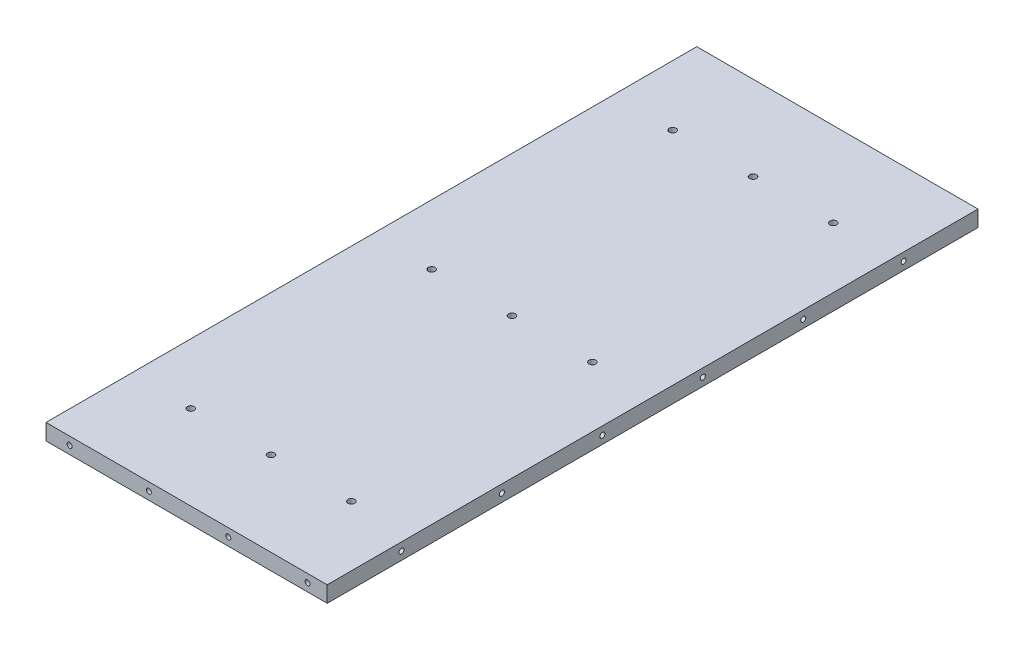
SolidWorks part; units mm, degrees
ref_plane "Front Plane" through (0, 0, 0) normal (0, 0, 1) x (1, 0, 0)
ref_plane "Top Plane" through (0, 0, 0) normal (0, 1, 0) x (1, 0, 0)
ref_plane "Right Plane" through (0, 0, 0) normal (1, 0, 0) x (0, 0, -1)
sketch "Sketch1" plane through (0, 0, 0) normal (0, 1, 0) x (1, 0, 0)
  line L1 (70, -162) -> (-70, -162)
  line L2 (70, -162) -> (70, 162)
  line L3 (70, 162) -> (-70, 162)
  line L4 (-70, -162) -> (-70, 162)
  line L5 (70, -162) -> (-70, 162) construction
  line L6 (70, 162) -> (-70, -162) construction
  point P0 (0, 0)
  dimension "D1" = 324
  dimension "D2" = 140
extrude "Boss-Extrude1" add sketch "Sketch1" along normal blind 8
sketch "Sketch2" plane through (0, 0, 162) normal (0, 0, 1) x (1, 0, 0)
  point P0 (60.25, 4)
  point P2 (20.75, 4)
  point P4 (-18.75, 4)
  point P6 (-58.25, 4)
  point P8 (-78, 4)
  point P10 (-78, 4)
  point P12 (-78, 4)
  point P14 (-78, 4)
  point P16 (-78, 4)
  point P18 (-78, 4)
hole_wizard "M3x0.5 Tapped Hole1" positions "Sketch3" profile "Sketch5" tap size "M3x0.5" standard "BSI"
sketch "Sketch3" plane through (0, 0, 162) normal (0, 0, 1) x (1, 0, 0)
  point P0 (60.25, 4)
  point P3 (20.75, 4)
  point P6 (-18.75, 4)
  point P9 (-58.25, 4)
sketch "Sketch5" plane through (60.25, 4, 162) normal (1, 0, 0) x (0, -1, 0)
  line L0 (0, 0) -> (0, 12.2511)
  line L1 (0, 12.2511) -> (1.25, 11.5)
  line L2 (1.25, 11.5) -> (1.25, 0)
  line L5 (1.25, 0) -> (0, 0)
  line L10 (0, 12.2511) -> (-1.25, 11.5) construction
  line L11 (0, -6.35) -> (0, 107.95) construction
  dimension "Tap Drill Dia." = 2.5
  dimension "Tap Drill Depth" = 11.5
  dimension "Drill Angle" = 118
cosmetic thread "Hole Thread1" parameters "D1"=10, "D2"=3.5
cosmetic thread "Hole Thread2" parameters "D1"=10, "D2"=3.5
cosmetic thread "Hole Thread3" parameters "D1"=10, "D2"=3.5
cosmetic thread "Hole Thread4" parameters "D1"=10, "D2"=3.5
sketch "Sketch6" plane through (-70, 0, 0) normal (-1, 0, 0) x (0, 0, 1)
  point P0 (125, 4)
  point P2 (75, 4)
  point P4 (25, 4)
  point P6 (-25, 4)
  point P8 (-75, 4)
  point P10 (-125, 4)
hole_wizard "M3x0.5 Tapped Hole2" positions "3DSketch1" profile "Sketch7" tap size "M3x0.5" standard "BSI"
sketch3d "3DSketch1"
  point P0 (-70, 4, -125)
  point P3 (-70, 4, -75)
  point P6 (-70, 4, -25)
  point P9 (-70, 4, 25)
  point P12 (-70, 4, 75)
  point P15 (-70, 4, 125)
sketch "Sketch7" plane through (-70, 4, -125) normal (0, 1, 0) x (0, 0, 1)
  line L0 (0, 0) -> (0, 12.2511)
  line L1 (0, 12.2511) -> (1.25, 11.5)
  line L2 (1.25, 11.5) -> (1.25, 0)
  line L5 (1.25, 0) -> (0, 0)
  line L10 (0, 12.2511) -> (-1.25, 11.5) construction
  line L11 (0, -6.35) -> (0, 107.95) construction
  dimension "Tap Drill Dia." = 2.5
  dimension "Tap Drill Depth" = 11.5
  dimension "Drill Angle" = 118
cosmetic thread "Hole Thread5" parameters "D1"=10, "D2"=3.5
cosmetic thread "Hole Thread6" parameters "D1"=10, "D2"=3.5
cosmetic thread "Hole Thread7" parameters "D1"=10, "D2"=3.5
cosmetic thread "Hole Thread8" parameters "D1"=10, "D2"=3.5
cosmetic thread "Hole Thread9" parameters "D1"=10, "D2"=3.5
cosmetic thread "Hole Thread10" parameters "D1"=10, "D2"=3.5
mirror "Mirror1" about plane through (0, 0, 0) normal (0, 0, 1) of "M3x0.5 Tapped Hole1"
mirror "Mirror2" about plane through (0, 0, 0) normal (1, 0, 0) of "M3x0.5 Tapped Hole2"
sketch "Sketch8" plane through (0, 8, 0) normal (0, 1, 0) x (1, 0, 0)
  point P0 (-40, 0)
  dimension "D1" = 40
hole_wizard "Ø3.4 (3.4) Diameter Hole1" positions "3DSketch2" profile "Sketch9" hole size "Ø3.4" standard "BSI" end condition through all
sketch3d "3DSketch2"
  point P0 (-40, 8, 0)
sketch "Sketch9" plane through (-40, 8, 0) normal (1, 0, 0) x (0, 0, 1)
  line L0 (0, 0) -> (0, 8)
  line L1 (0, 8) -> (1.7, 8)
  line L2 (1.7, 8) -> (1.7, 0)
  line L5 (1.7, 0) -> (0, 0)
  line L11 (0, -6.35) -> (0, 107.95) construction
  dimension "Thru Hole Dia." = 3.4
  dimension "Thru Hole Depth" = 8
pattern_linear "LPattern1" count 2 spacing 120 along (0, 0, 1) count 3 spacing 40 along (1, 0, 0) of "Ø3.4 (3.4) Diameter Hole1"
mirror "Mirror3" about plane through (0, 0, 0) normal (0, 0, 1) of "LPattern1"
